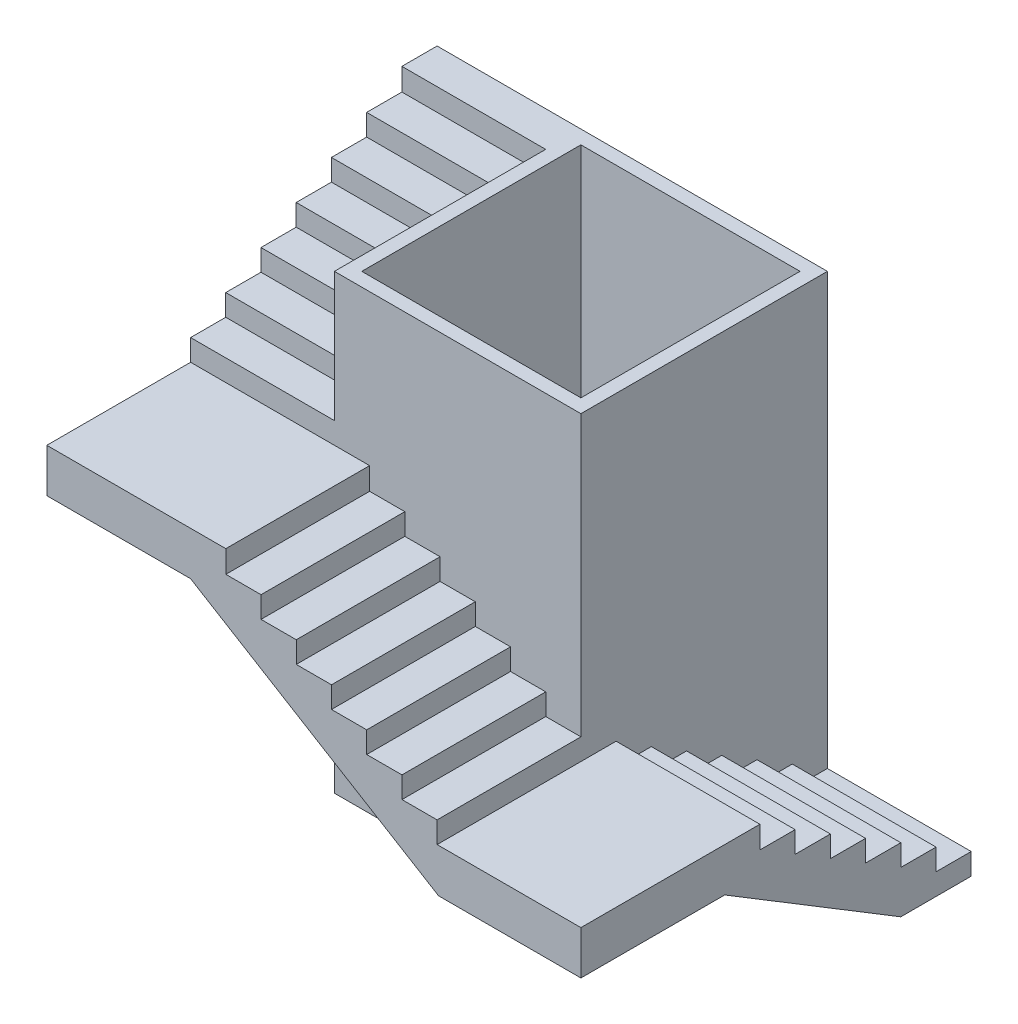
SolidWorks part; units mm, degrees
ref_plane "Front Plane" through (0, 0, 0) normal (0, 0, 1) x (1, 0, 0)
ref_plane "Top Plane" through (0, 0, 0) normal (0, 1, 0) x (1, 0, 0)
ref_plane "Right Plane" through (0, 0, 0) normal (1, 0, 0) x (0, 0, -1)
sketch "Sketch1" plane through (0, 0, 0) normal (0, 1, 0) x (1, 0, 0)
  line L1 (-9372.6, 3048) -> (9372.6, 3048)
  line L2 (-9372.6, 3048) -> (-9372.6, -3048)
  line L3 (-9372.6, -3048) -> (9372.6, -3048)
  line L4 (9372.6, 3048) -> (9372.6, -3048)
  line L5 (-9372.6, 3048) -> (9372.6, -3048) construction
  line L6 (-9372.6, -3048) -> (9372.6, 3048) construction
  line L7 (-914.4, -1066.8) -> (914.4, -1066.8)
  line L8 (-914.4, -1066.8) -> (-914.4, -2895.6)
  line L9 (-914.4, -2895.6) -> (914.4, -2895.6)
  line L10 (914.4, -1066.8) -> (914.4, -2895.6)
  line L11 (-914.4, -1066.8) -> (914.4, -2895.6) construction
  line L12 (-914.4, -2895.6) -> (914.4, -1066.8) construction
  line L13 (-1981.2, -3962.4) -> (1981.2, -3962.4)
  line L16 (-1981.2, -1066.8) -> (1981.2, -1066.8)
  line L17 (-1981.2, -1066.8) -> (-1981.2, -3962.4)
  line L18 (-1981.2, 0) -> (-1981.2, -3962.4) construction
  line L19 (1981.2, 342.9) -> (1981.2, -3962.4)
  line L20 (1981.2, 0) -> (1981.2, -3962.4) construction
  line L21 (-1981.2, 0) -> (1981.2, 0) construction
  line L22 (-914.4, 228.6) -> (1981.2, 228.6) construction
  line L23 (-1977.0221, -3048) -> (-9372.6, -3048) construction
  line L24 (-5562.6, 1828.8) -> (-5562.6, 1808.9756) construction
  line L25 (-1981.2, 3048) -> (-1981.2, -1066.8)
  line L26 (-9144, 1828.8) -> (-1981.2, 1828.8) construction
  line L35 (-9144, 2819.4) -> (9144, 2819.4)
  line L36 (9144, 2819.4) -> (9144, -2819.4)
  line L37 (-9144, -2819.4) -> (9144, -2819.4)
  line L38 (-9144, 2819.4) -> (-9144, -2819.4)
  line L43 (-1981.2, 342.9) -> (2257.9209, 342.9) construction
  line L48 (-5448.3, 1828.8) -> (-5448.3, 1771.8049)
  line L49 (-1981.2, 228.6) -> (2257.9209, 228.6) construction
  line L50 (-914.4, 114.3) -> (1981.2, 114.3)
  line L51 (-1981.2, 114.3) -> (2257.9209, 114.3) construction
  line L52 (-914.4, 342.9) -> (1981.2, 342.9)
  line L53 (-9144, 1524) -> (-5562.6, 1524) construction
  line L54 (-5562.6, 1524) -> (-5562.6, -2819.4) construction
  line L59 (5562.6, 228.6) -> (1981.2, 228.6)
  line L60 (-9372.6, 3048) -> (-5562.6, 3048) construction
  line L61 (-5448.3, 1828.8) -> (-5448.3, -2819.4) construction
  line L62 (-9372.6, 3048) -> (-9372.6, 1524) construction
  line L63 (-5562.6, 1828.8) -> (-5562.6, -2819.4) construction
  line L64 (-9372.6, 1524) -> (-5562.6, 1524) construction
  line L65 (-5562.6, 3048) -> (-5562.6, 1524) construction
  line L70 (9372.6, -3048) -> (5562.6, -3048)
  line L71 (9372.6, -3048) -> (9372.6, 342.9)
  line L73 (5562.6, -3048) -> (5562.6, 228.6)
  line L74 (1981.2, 228.6) -> (1981.2, 2819.4)
  line L75 (1981.2, 2819.4) -> (8001, 2819.4)
  line L76 (8001, 2819.4) -> (8001, 228.6)
  line L77 (-914.4, -1066.8) -> (-914.4, 342.9)
  line L78 (-5613.4, 3048) -> (-5613.4, 1574.8)
  line L79 (-9144, 1473.2) -> (-5613.4, 1473.2)
  line L80 (-5613.4, 1473.2) -> (-5613.4, -2819.4)
  line L81 (-5511.8, 3048) -> (-5511.8, 1524)
  line L82 (-9144, 1574.8) -> (-5613.4, 1574.8)
  line L83 (-5511.8, 1574.8) -> (-5511.8, -2819.4)
  line L84 (-5613.4, 3048) -> (-5613.4, 1524) construction
  line L85 (-812.8, -1168.4) -> (812.8, -1168.4)
  line L86 (-9144, 1574.8) -> (-5511.8, 1574.8) construction
  line L87 (812.8, -1168.4) -> (812.8, -2794)
  line L88 (-812.8, -2794) -> (812.8, -2794)
  line L89 (-812.8, -1168.4) -> (-812.8, -2794)
  line L90 (-1143, 342.9) -> (-1143, -1066.8)
  line L91 (-1143, 342.9) -> (-914.4, 342.9)
  line L92 (1981.2, 1206.5) -> (3810, 1206.5)
  line L93 (3810, 1206.5) -> (3810, 2819.4)
  line L94 (5676.9, -3048) -> (5676.9, 342.9)
  line L95 (5676.9, 342.9) -> (1981.2, 342.9)
  line L96 (5448.3, -3048) -> (5448.3, 114.3)
  line L97 (5448.3, 114.3) -> (1981.2, 114.3)
  line L98 (7950.2, 2819.4) -> (7950.2, 228.6)
  line L99 (8051.8, 2819.4) -> (8051.8, 228.6)
  line L100 (1981.2, 1308.1) -> (3810, 1308.1)
  line L101 (3708.4, 1206.5) -> (3708.4, 2819.4)
  line L102 (5676.9, 342.9) -> (9144, 342.9)
  line L103 (5676.9, 241.3) -> (9144, 241.3)
  line L104 (1879.6, 228.6) -> (1879.6, 2819.4)
  point P0 (0, 0)
  point P6 (0, -1981.2)
  point P18 (0, -1066.8)
  point P21 (533.4, 228.6)
  point P52 (0, 2819.4)
  dimension "D1" = 18745.2
  dimension "D2" = 6096
  dimension "D3" = 1828.8
  dimension "D4" = 1828.8
  dimension "D5" = 914.4
  dimension "D7" = 1143
  dimension "D8" = 1219.2
  dimension "D9" = 3810
  dimension "D10" = 1524
  dimension "D13" = 114.3
  dimension "D11" = 3810
  dimension "D14" = 114.3
  dimension "D16" = 3810
  dimension "D17" = 101.6
  dimension "D18" = 50.8
  dimension "D19" = 50.8
  dimension "D21" = 228.6
  dimension "D22" = 1828.8
  dimension "D23" = 863.6
  dimension "D30" = 101.6
  dimension "D6" = 1066.8
  dimension "D12" = 228.6
  dimension "D15" = 114.3
  dimension "D20" = 101.6
  dimension "D24" = 114.3
  dimension "D25" = 114.3
  dimension "D26" = 50.8
  dimension "D27" = 50.8
  dimension "D28" = 101.6
  dimension "D29" = 101.6
ref_plane "Plane1" through (0, 3962.4, 0) normal (0, 1, 0) x (1, 0, 0)
sketch "Sketch2" plane through (0, 3962.4, 0) normal (0, 1, 0) x (1, 0, 0)
  line L0 (-9372.6, 3048) -> (9372.6, 3048)
  line L1 (-9372.6, 3048) -> (-9372.6, -3048)
  line L2 (-9372.6, -3048) -> (9372.6, -3048)
  line L3 (9372.6, 3048) -> (9372.6, -3048)
  line L4 (-9372.6, 3048) -> (9372.6, -3048) construction
  line L5 (-9372.6, -3048) -> (9372.6, 3048) construction
  line L6 (-914.4, -1066.8) -> (914.4, -1066.8)
  line L7 (-914.4, -1066.8) -> (-914.4, -2895.6)
  line L8 (-914.4, -2895.6) -> (914.4, -2895.6)
  line L9 (914.4, -1066.8) -> (914.4, -2895.6)
  line L10 (-914.4, -1066.8) -> (914.4, -2895.6) construction
  line L11 (-914.4, -2895.6) -> (914.4, -1066.8) construction
  line L12 (-1981.2, -3962.4) -> (1981.2, -3962.4)
  line L13 (-1981.2, -1066.8) -> (1981.2, -1066.8)
  line L14 (-1981.2, -1066.8) -> (-1981.2, -3962.4)
  line L15 (1981.2, -1066.8) -> (1981.2, -3962.4)
  line L16 (-1981.2, 152.4) -> (2257.9209, 152.4) construction
  line L17 (-2099.6292, -3048) -> (-9372.6, -3048) construction
  line L18 (-5562.6, 1828.8) -> (-5562.6, -2819.4) construction
  line L19 (-9144, 1828.8) -> (-1981.2, 1828.8) construction
  line L20 (-9144, 2819.4) -> (8898.7858, 2819.4)
  line L21 (8898.7858, 2819.4) -> (8898.7858, -2819.4)
  line L22 (-9144, -2819.4) -> (8898.7858, -2819.4)
  line L23 (-9144, 2819.4) -> (-9144, -2819.4)
  line L24 (-914.4, -2895.6) -> (914.4, -2895.6) construction
  line L25 (-9372.6, 3048) -> (-6781.8, 3048)
  line L26 (-9372.6, 3048) -> (-9372.6, 1524)
  line L27 (-9372.6, 1524) -> (-6781.8, 1524)
  line L28 (-6781.8, 3048) -> (-6781.8, 1524)
  line L32 (0, 0) -> (0, 1033.0674) construction
  line L33 (-884.6071, 2819.4) -> (-884.6071, 1485.9)
  line L34 (-884.6071, 1485.9) -> (639.3929, 1485.9)
  line L35 (639.3929, 2819.4) -> (639.3929, 1485.9)
  line L36 (-253.2357, 3048) -> (639.3929, 1485.9) construction
  line L37 (-884.6071, 1485.9) -> (8.0215, 3048) construction
  line L38 (9144, 1828.8) -> (1981.2, 1828.8) construction
  line L39 (5562.6, 1828.8) -> (5562.6, -2819.4) construction
  line L42 (-1981.2, 1828.8) -> (-1981.2, -1066.8)
  line L43 (1981.2, 1828.8) -> (1981.2, -1066.8)
  line L44 (-9372.6, -3048) -> (9372.6, -3048) construction
  line L45 (9372.6, 3048) -> (9372.6, -3048) construction
  point P0 (0, 0)
  point P5 (0, -1981.2)
  point P15 (0, -1066.8)
  point P18 (138.3605, 152.4)
  point P43 (-122.6071, 2819.4)
  point P56 (0, 0)
  dimension "D1" = 18745.2
  dimension "D2" = 6096
  dimension "D3" = 1828.8
  dimension "D4" = 1828.8
  dimension "D5" = 1219.2
  dimension "D6" = 1219.2
  dimension "D7" = 1524
  dimension "D8" = 2590.8
  dimension "D9" = 914.4
  dimension "D11" = 228.6
extrude "Boss-Extrude1" add sketch "Sketch1" along normal blind 3352.8 contours L8 L37 L10 L7 L89 L85 L87 L88 | L37 L8 L9 L10
sketch "Sketch3" plane through (914.4, 0, 0) normal (1, 0, 0) x (0, 0, -1)
  line L0 (-1066.8, 0) -> (-1066.8, 237.4907)
  line L1 (-1066.8, 3352.8) -> (-1066.8, 0) construction
  line L2 (-2895.6, 1117.6) -> (-1066.8, 1117.6) construction
  line L3 (-2895.6, 3352.8) -> (-2895.6, 0) construction
  line L4 (-2634.3429, 1117.6) -> (-2634.3429, 0) construction
  line L5 (2819.4, 0) -> (-2819.4, 0) construction
  line L6 (-2372.9769, 1117.6) -> (-2372.9769, 0) construction
  line L7 (-2111.6109, 1117.6) -> (-2111.6109, 0) construction
  line L8 (-1850.2449, 1117.6) -> (-1850.2449, 0) construction
  line L9 (-1588.8789, 1117.6) -> (-1588.8789, 0) construction
  line L10 (-1327.5129, 1117.6) -> (-1327.5129, 0) construction
  line L11 (-1066.1469, 1117.6) -> (-1066.1469, 0) construction
  line L12 (-2895.6, 2235.2) -> (-2895.6, 0)
  line L13 (-2895.6, 952.5) -> (-1066.1469, 952.5) construction
  line L14 (-2895.6, 793.75) -> (-1066.1469, 793.75) construction
  line L15 (-2895.6, 635) -> (-1066.1469, 635) construction
  line L16 (-2895.6, 476.25) -> (-1066.1469, 476.25) construction
  line L17 (-2895.6, 317.5) -> (-1066.1469, 317.5) construction
  line L18 (-2895.6, 158.75) -> (-1066.1469, 158.75) construction
  line L19 (-2895.6, 0) -> (-1066.1469, 0) construction
  line L20 (-2895.6, 1117.6) -> (-2634.3429, 1117.6)
  line L21 (-2634.3429, 1117.6) -> (-2634.3429, 952.5)
  line L22 (-2634.3429, 952.5) -> (-2372.9769, 952.5)
  line L23 (-2372.9769, 952.5) -> (-2372.9769, 793.75)
  line L24 (-2372.9769, 793.75) -> (-2111.6109, 793.75)
  line L25 (-2111.6109, 793.75) -> (-2111.6109, 635)
  line L26 (-2111.6109, 635) -> (-1850.2449, 635)
  line L27 (-1850.2449, 635) -> (-1850.2449, 476.25)
  line L28 (-1850.2449, 476.25) -> (-1588.8789, 476.25)
  line L29 (-1588.8789, 476.25) -> (-1588.8789, 317.5)
  line L30 (-1588.8789, 317.5) -> (-1327.5129, 317.5)
  line L31 (-1327.5129, 317.5) -> (-1327.5129, 158.75)
  line L32 (-1327.5129, 158.75) -> (-1066.1469, 158.75)
  line L33 (-2895.6, 793.75) -> (-1588.8789, 0)
  point P29 (-2895.6, 1117.6)
  point P32 (-2895.6, 952.5)
  line M12 (-2895.6, 0) -> (-1066.8, 0)
  line M13 (-1066.8, 0) -> (-1066.8, 3352.8)
  dimension "D1" = 261.2571
  dimension "D3" = 165.1
  dimension "D4" = 7
  dimension "D2" = 7
extrude "Boss-Extrude2" add sketch "Sketch3" along normal blind 1066.8 contours L12 L33 L32 L31 L30 L29 L28 L27 L26 L25 L24 L23 L22 L21 L20 M12 M13
sketch "Sketch4" plane through (0, 0, 2895.6) normal (0, 0, 1) x (1, 0, 0)
  line L0 (914.4, 1117.6) -> (-914.4, 1117.6)
  line L1 (-914.4, 3352.8) -> (-914.4, 0) construction
  line L2 (914.4, 1117.6) -> (914.4, 1355.0907)
  line L3 (-914.4, 2235.2) -> (914.4, 2235.2) construction
  line L4 (-653.1429, 2235.2) -> (-653.1429, 1117.6) construction
  line L5 (-391.7769, 2235.2) -> (-391.7769, 1117.6) construction
  line L6 (-130.4109, 2235.2) -> (-130.4109, 1117.6) construction
  line L7 (130.9551, 2235.2) -> (130.9551, 1117.6) construction
  line L8 (392.3211, 2235.2) -> (392.3211, 1117.6) construction
  line L9 (653.6871, 2235.2) -> (653.6871, 1117.6) construction
  line L10 (915.0531, 2235.2) -> (915.0531, 1117.6) construction
  line L11 (-914.4, 3352.8) -> (-914.4, 1117.6)
  line L12 (-914.4, 2070.1) -> (915.0531, 2070.1) construction
  line L13 (-914.4, 1911.35) -> (915.0531, 1911.35) construction
  line L14 (-914.4, 1752.6) -> (915.0531, 1752.6) construction
  line L15 (-914.4, 1593.85) -> (915.0531, 1593.85) construction
  line L16 (-914.4, 1435.1) -> (915.0531, 1435.1) construction
  line L17 (-914.4, 1276.35) -> (915.0531, 1276.35) construction
  line L18 (-914.4, 1117.6) -> (915.0531, 1117.6) construction
  line L19 (-914.4, 2235.2) -> (-653.1429, 2235.2)
  line L20 (-653.1429, 2235.2) -> (-653.1429, 2070.1)
  line L21 (-653.1429, 2070.1) -> (-391.7769, 2070.1)
  line L22 (-391.7769, 2070.1) -> (-391.7769, 1911.35)
  line L23 (-391.7769, 1911.35) -> (-130.4109, 1911.35)
  line L24 (-130.4109, 1911.35) -> (-130.4109, 1752.6)
  line L25 (-130.4109, 1752.6) -> (130.9551, 1752.6)
  line L26 (130.9551, 1752.6) -> (130.9551, 1593.85)
  line L27 (130.9551, 1593.85) -> (392.3211, 1593.85)
  line L28 (392.3211, 1593.85) -> (392.3211, 1435.1)
  line L29 (392.3211, 1435.1) -> (653.6871, 1435.1)
  line L30 (653.6871, 1435.1) -> (653.6871, 1276.35)
  line L31 (653.6871, 1276.35) -> (915.0531, 1276.35)
  line L32 (-914.4, 1911.35) -> (392.3211, 1117.6)
  line L41 (-914.4, 0) -> (914.4, 0)
  line L42 (914.4, 0) -> (914.4, 793.75)
  line L43 (914.4, 793.75) -> (1981.2, 793.75)
  line L44 (1981.2, 793.75) -> (1981.2, 1117.6)
  line L45 (1981.2, 1117.6) -> (914.4, 1117.6)
  line L46 (914.4, 1117.6) -> (914.4, 3352.8)
  line L47 (914.4, 3352.8) -> (-914.4, 3352.8)
  line L48 (-914.4, 3352.8) -> (-914.4, 0)
  line L49 (-914.4, 0) -> (914.4, 0)
  line L50 (914.4, 0) -> (914.4, 793.75)
  line L51 (914.4, 793.75) -> (1981.2, 793.75)
  line L52 (1981.2, 793.75) -> (1981.2, 1117.6)
  line L53 (1981.2, 1117.6) -> (914.4, 1117.6)
  line L54 (914.4, 1117.6) -> (914.4, 3352.8)
  line L55 (914.4, 3352.8) -> (-914.4, 3352.8)
  line L56 (-914.4, 3352.8) -> (-914.4, 0)
  point P26 (-914.4, 2235.2)
  point P29 (-914.4, 2070.1)
  line M18 (914.4, 1117.6) -> (914.4, 3352.8)
  dimension "D1" = 165.1
  dimension "D3" = 158.75
  dimension "D2" = 0
extrude "Boss-Extrude3" add sketch "Sketch4" along normal blind 1066.8 contours L11 L32 L0 L31 L30 L29 L28 L27 L26 L25 L24 L23 L22 L21 L20 L19 M18
sketch "Sketch5" plane through (0, 1117.6, 0) normal (0, 1, 0) x (1, 0, 0)
  line L1 (914.4, -2895.6) -> (1981.2, -2895.6)
  line L2 (914.4, -2895.6) -> (914.4, -3962.4)
  line L3 (914.4, -3962.4) -> (1981.2, -3962.4)
  line L4 (1981.2, -2895.6) -> (1981.2, -3962.4)
  line L8 (914.4, -2895.6) -> (392.3211, -2895.6)
  line L9 (914.4, -3962.4) -> (914.4, -2895.6)
  line L10 (392.3211, -3962.4) -> (914.4, -3962.4)
  line L11 (392.3211, -2895.6) -> (392.3211, -3962.4)
  line L12 (914.4, -2895.6) -> (392.3211, -2895.6)
  line L13 (914.4, -3962.4) -> (914.4, -2895.6)
  line L14 (392.3211, -3962.4) -> (914.4, -3962.4)
  line L15 (392.3211, -2895.6) -> (392.3211, -3962.4)
  line M6 (914.4, -2895.6) -> (1981.2, -2895.6)
  dimension "D1" = 0
extrude "Boss-Extrude5" add sketch "Sketch5" against normal blind 323.85 contours L4 L2 L3 M6 | L12 L15 L14 L2
sketch "Sketch6" plane through (-914.4, 0, 0) normal (-1, 0, 0) x (0, 0, 1)
  line L0 (2895.6, 2235.2) -> (1066.8, 2235.2)
  line L1 (1066.8, 3352.8) -> (1066.8, 0) construction
  line L2 (2895.6, 2235.2) -> (2895.6, 2472.6907)
  line L3 (1066.8, 3352.8) -> (2895.6, 3352.8) construction
  line L4 (1328.0571, 3352.8) -> (1328.0571, 2235.2) construction
  line L5 (1589.4231, 3352.8) -> (1589.4231, 2235.2) construction
  line L6 (1850.7891, 3352.8) -> (1850.7891, 2235.2) construction
  line L7 (2112.1551, 3352.8) -> (2112.1551, 2235.2) construction
  line L8 (2373.5211, 3352.8) -> (2373.5211, 2235.2) construction
  line L9 (2634.8871, 3352.8) -> (2634.8871, 2235.2) construction
  line L10 (2896.2531, 3352.8) -> (2896.2531, 2235.2) construction
  line L11 (1066.8, 4470.4) -> (1066.8, 2235.2)
  line L12 (1066.8, 3187.7) -> (2896.2531, 3187.7) construction
  line L13 (1066.8, 3028.95) -> (2896.2531, 3028.95) construction
  line L14 (1066.8, 2870.2) -> (2896.2531, 2870.2) construction
  line L15 (1066.8, 2711.45) -> (2896.2531, 2711.45) construction
  line L16 (1066.8, 2552.7) -> (2896.2531, 2552.7) construction
  line L17 (1066.8, 2393.95) -> (2896.2531, 2393.95) construction
  line L18 (1066.8, 2235.2) -> (2896.2531, 2235.2) construction
  line L19 (1066.8, 3352.8) -> (1328.0571, 3352.8)
  line L20 (1328.0571, 3352.8) -> (1328.0571, 3187.7)
  line L21 (1328.0571, 3187.7) -> (1589.4231, 3187.7)
  line L22 (1589.4231, 3187.7) -> (1589.4231, 3028.95)
  line L23 (1589.4231, 3028.95) -> (1850.7891, 3028.95)
  line L24 (1850.7891, 3028.95) -> (1850.7891, 2870.2)
  line L25 (1850.7891, 2870.2) -> (2112.1551, 2870.2)
  line L26 (2112.1551, 2870.2) -> (2112.1551, 2711.45)
  line L27 (2112.1551, 2711.45) -> (2373.5211, 2711.45)
  line L28 (2373.5211, 2711.45) -> (2373.5211, 2552.7)
  line L29 (2373.5211, 2552.7) -> (2634.8871, 2552.7)
  line L30 (2634.8871, 2552.7) -> (2634.8871, 2393.95)
  line L31 (2634.8871, 2393.95) -> (2896.2531, 2393.95)
  line L32 (1066.8, 3028.95) -> (2373.5211, 2235.2)
  point P26 (1066.8, 3352.8)
  point P29 (1066.8, 3187.7)
  line M7 (2895.6, 2235.2) -> (2895.6, 3352.8)
  dimension "D1" = 165.1
extrude "Boss-Extrude6" add sketch "Sketch6" along normal blind 1066.8 contours L11 L32 L0 L31 L30 L29 L28 L27 L26 L25 L24 L23 L22 L21 L20 L19 M7
sketch "Sketch7" plane through (0, 2235.2, 0) normal (0, -1, 0) x (1, 0, 0)
  line L0 (-1981.2, 1066.8) -> (-1981.2, 3962.4) construction
  line L1 (-1981.2, 3962.4) -> (1981.2, 3962.4) construction
  line L2 (-1981.2, 1066.8) -> (-1981.2, 3962.4)
  line L3 (-1981.2, 3962.4) -> (1981.2, 3962.4)
  line L4 (-914.4, 2373.5211) -> (-914.4, 2895.6)
  line L5 (-914.4, 2895.6) -> (-1981.2, 2895.6)
  line L6 (-1981.2, 2895.6) -> (-1981.2, 2373.5211)
  line L7 (-1981.2, 2373.5211) -> (-914.4, 2373.5211)
  line L8 (-914.4, 2373.5211) -> (-914.4, 2895.6)
  line L9 (-914.4, 2895.6) -> (-1981.2, 2895.6)
  line L10 (-1981.2, 2895.6) -> (-1981.2, 2373.5211)
  line L11 (-1981.2, 2373.5211) -> (-914.4, 2373.5211)
  line L12 (-914.4, 3962.4) -> (-914.4, 2895.6)
  line M5 (-914.4, 2373.5211) -> (-914.4, 2895.6)
  line M6 (-914.4, 2895.6) -> (-1981.2, 2895.6)
  line M7 (-1981.2, 2895.6) -> (-1981.2, 2373.5211)
  line M8 (-1981.2, 2373.5211) -> (-914.4, 2373.5211)
  dimension "D1" = 0
extrude "Boss-Extrude7" add sketch "Sketch7" along normal blind 323.85 contours L12 L3 L2 M6 | M8 M5 M6 M7
sketch "Sketch8" plane through (0, 0, 3962.4) normal (0, 0, 1) x (1, 0, 0)
  line L0 (-914.4, 1911.35) -> (392.3211, 1117.6) construction
  line L1 (-914.4, 1911.35) -> (925.4634, 793.75)
  line L2 (392.3211, 793.75) -> (1981.2, 793.75) construction
  line L3 (392.3211, 793.75) -> (1981.2, 793.75)
  line L4 (392.3211, 793.75) -> (392.3211, 1117.6) construction
  line L5 (392.3211, 793.75) -> (392.3211, 1117.6)
  line M5 (392.3211, 1117.6) -> (392.3211, 793.75)
  line M6 (392.3211, 793.75) -> (1981.2, 793.75)
extrude "Cut-Extrude1" cut sketch "Sketch8" against normal blind 1066.8 contours L1 M5 M6
sketch "Sketch9" plane through (-1981.2, 0, 0) normal (-1, 0, 0) x (0, 0, 1)
  line L20 (1066.8, 3352.8) -> (1066.8, 3028.95)
  line L21 (1066.8, 3028.95) -> (2373.5211, 2235.2)
  line L22 (2373.5211, 2235.2) -> (2373.5211, 1911.35)
  line L23 (2373.5211, 1911.35) -> (3962.4, 1911.35)
  line L24 (3962.4, 1911.35) -> (3962.4, 2235.2)
  line L25 (3962.4, 2235.2) -> (2895.6, 2235.2)
  line L26 (2895.6, 2235.2) -> (2895.6, 2393.95)
  line L27 (2895.6, 2393.95) -> (2634.8871, 2393.95)
  line L28 (2634.8871, 2393.95) -> (2634.8871, 2552.7)
  line L29 (2634.8871, 2552.7) -> (2373.5211, 2552.7)
  line L30 (2373.5211, 2552.7) -> (2373.5211, 2711.45)
  line L31 (2373.5211, 2711.45) -> (2112.1551, 2711.45)
  line L32 (2112.1551, 2711.45) -> (2112.1551, 2870.2)
  line L33 (2112.1551, 2870.2) -> (1850.7891, 2870.2)
  line L34 (1850.7891, 2870.2) -> (1850.7891, 3028.95)
  line L35 (1850.7891, 3028.95) -> (1589.4231, 3028.95)
  line L36 (1589.4231, 3028.95) -> (1589.4231, 3187.7)
  line L37 (1589.4231, 3187.7) -> (1328.0571, 3187.7)
  line L38 (1328.0571, 3187.7) -> (1328.0571, 3352.8)
  line L39 (1328.0571, 3352.8) -> (1066.8, 3352.8)
  line L40 (1066.8, 3352.8) -> (1066.8, 3028.95)
  line L41 (1066.8, 3028.95) -> (2906.6634, 1911.35)
  line L42 (2373.5211, 2235.2) -> (2373.5211, 1911.35)
  line L43 (2373.5211, 1911.35) -> (3962.4, 1911.35)
  line L44 (3962.4, 1911.35) -> (3962.4, 2235.2)
  line L45 (3962.4, 2235.2) -> (2895.6, 2235.2)
  line L46 (2895.6, 2235.2) -> (2895.6, 2393.95)
  line L47 (2895.6, 2393.95) -> (2634.8871, 2393.95)
  line L48 (2634.8871, 2393.95) -> (2634.8871, 2552.7)
  line L49 (2634.8871, 2552.7) -> (2373.5211, 2552.7)
  line L50 (2373.5211, 2552.7) -> (2373.5211, 2711.45)
  line L51 (2373.5211, 2711.45) -> (2112.1551, 2711.45)
  line L52 (2112.1551, 2711.45) -> (2112.1551, 2870.2)
  line L53 (2112.1551, 2870.2) -> (1850.7891, 2870.2)
  line L54 (1850.7891, 2870.2) -> (1850.7891, 3028.95)
  line L55 (1850.7891, 3028.95) -> (1589.4231, 3028.95)
  line L56 (1589.4231, 3028.95) -> (1589.4231, 3187.7)
  line L57 (1589.4231, 3187.7) -> (1328.0571, 3187.7)
  line L58 (1328.0571, 3187.7) -> (1328.0571, 3352.8)
  line L59 (1328.0571, 3352.8) -> (1066.8, 3352.8)
  line M23 (2373.5211, 2235.2) -> (2373.5211, 1911.35)
  line M24 (2373.5211, 1911.35) -> (3962.4, 1911.35)
  dimension "D1" = 0
extrude "Cut-Extrude2" cut sketch "Sketch9" against normal blind 1066.8 contours L41 M23 M24
sketch "Sketch10" plane through (0, 0, 0) normal (0, 1, 0) x (1, 0, 0)
  line L0 (-1981.2, -1066.8) -> (1981.2, -1066.8) construction
  line L1 (-914.4, -1066.8) -> (-914.4, 342.9) construction
  line L2 (9372.6, -3048) -> (5562.6, -3048) construction
  line L3 (5562.6, -3048) -> (5562.6, 228.6) construction
  line L4 (5562.6, 228.6) -> (1981.2, 228.6) construction
  line L5 (1981.2, 228.6) -> (1981.2, 2819.4) construction
  line L6 (1981.2, 2819.4) -> (8001, 2819.4) construction
  line L7 (8001, 2819.4) -> (8001, 228.6) construction
  line L10 (-1981.2, 3048) -> (-1981.2, -1066.8) construction
  line L11 (-1981.2, -1066.8) -> (-1981.2, -3962.4) construction
  line L12 (-1981.2, -3962.4) -> (1981.2, -3962.4) construction
  line L13 (1981.2, 342.9) -> (1981.2, -3962.4) construction
  line L14 (-914.4, 342.9) -> (1981.2, 342.9) construction
  line L15 (-5613.4, 3048) -> (-5613.4, 1574.8) construction
  line L16 (-9144, 1574.8) -> (-5613.4, 1574.8) construction
  line L17 (-914.4, 114.3) -> (1981.2, 114.3) construction
  line L18 (1981.2, 1206.5) -> (3810, 1206.5) construction
  line L19 (3810, 1206.5) -> (3810, 2819.4) construction
  line L20 (-9144, 1473.2) -> (-5613.4, 1473.2) construction
  line L21 (-5613.4, 1473.2) -> (-5613.4, -2819.4) construction
  line L22 (-1143, 342.9) -> (-1143, -1066.8) construction
  line L23 (-1143, 342.9) -> (-914.4, 342.9) construction
  line L24 (-5511.8, 1574.8) -> (-5511.8, -2819.4) construction
  line L25 (-5511.8, 3048) -> (-5511.8, 1524) construction
  line L26 (5676.9, 241.3) -> (9144, 241.3) construction
  line L27 (5676.9, 342.9) -> (9144, 342.9) construction
  line L28 (3708.4, 1206.5) -> (3708.4, 2819.4) construction
  line L29 (1981.2, 1308.1) -> (3810, 1308.1) construction
  line L30 (8051.8, 2819.4) -> (8051.8, 228.6) construction
  line L31 (7950.2, 2819.4) -> (7950.2, 228.6) construction
  line L32 (5448.3, -3048) -> (5448.3, 114.3) construction
  line L33 (5448.3, 114.3) -> (1981.2, 114.3) construction
  line L34 (5676.9, 342.9) -> (1981.2, 342.9) construction
  line L35 (5676.9, -3048) -> (5676.9, 342.9) construction
  line L36 (1879.6, 228.6) -> (1879.6, 2819.4) construction
  line L37 (-914.4, -1066.8) -> (914.4, -1066.8) construction
  line L38 (914.4, -1066.8) -> (914.4, -2895.6) construction
  line L39 (-914.4, -2895.6) -> (914.4, -2895.6) construction
  line L40 (-914.4, -1066.8) -> (-914.4, -2895.6) construction
  line L41 (9372.6, 3048) -> (9372.6, -3048) construction
  line L42 (-9372.6, 3048) -> (9372.6, 3048) construction
  line L43 (-9372.6, 3048) -> (-9372.6, -3048) construction
  line L44 (-9372.6, -3048) -> (9372.6, -3048) construction
  line L45 (-9144, 2819.4) -> (9144, 2819.4) construction
  line L46 (9144, 2819.4) -> (9144, -2819.4) construction
  line L47 (-9144, -2819.4) -> (9144, -2819.4) construction
  line L48 (-9144, 2819.4) -> (-9144, -2819.4) construction
  line L49 (-812.8, -1168.4) -> (812.8, -1168.4) construction
  line L50 (812.8, -1168.4) -> (812.8, -2794) construction
  line L51 (-812.8, -2794) -> (812.8, -2794) construction
  line L52 (-812.8, -1168.4) -> (-812.8, -2794) construction
  line L53 (-1981.2, -1066.8) -> (1981.2, -1066.8)
  line L54 (-914.4, -1066.8) -> (-914.4, 342.9)
  line L55 (9372.6, -3048) -> (5562.6, -3048)
  line L56 (5562.6, -3048) -> (5562.6, 228.6)
  line L57 (5562.6, 228.6) -> (1981.2, 228.6)
  line L58 (1981.2, 228.6) -> (1981.2, 2819.4)
  line L59 (1981.2, 2819.4) -> (8001, 2819.4)
  line L60 (8001, 2819.4) -> (8001, 228.6)
  line L63 (-1981.2, 3048) -> (-1981.2, -1066.8)
  line L64 (-1981.2, -1066.8) -> (-1981.2, -3962.4)
  line L65 (-1981.2, -3962.4) -> (1981.2, -3962.4)
  line L66 (1981.2, 342.9) -> (1981.2, -3962.4)
  line L67 (-914.4, 342.9) -> (1981.2, 342.9)
  line L68 (-5613.4, 3048) -> (-5613.4, 1574.8)
  line L69 (-9144, 1574.8) -> (-5613.4, 1574.8)
  line L70 (-914.4, 114.3) -> (1981.2, 114.3)
  line L71 (1981.2, 1206.5) -> (3810, 1206.5)
  line L72 (3810, 1206.5) -> (3810, 2819.4)
  line L73 (-9144, 1473.2) -> (-5613.4, 1473.2)
  line L74 (-5613.4, 1473.2) -> (-5613.4, -2819.4)
  line L75 (-1143, 342.9) -> (-1143, -1066.8)
  line L76 (-1143, 342.9) -> (-914.4, 342.9)
  line L77 (-5511.8, 1574.8) -> (-5511.8, -2819.4)
  line L78 (-5511.8, 3048) -> (-5511.8, 1524)
  line L79 (5676.9, 241.3) -> (9144, 241.3)
  line L80 (5676.9, 342.9) -> (9144, 342.9)
  line L81 (3708.4, 1206.5) -> (3708.4, 2819.4)
  line L82 (1981.2, 1308.1) -> (3810, 1308.1)
  line L83 (8051.8, 2819.4) -> (8051.8, 228.6)
  line L84 (7950.2, 2819.4) -> (7950.2, 228.6)
  line L85 (5448.3, -3048) -> (5448.3, 114.3)
  line L86 (5448.3, 114.3) -> (1981.2, 114.3)
  line L87 (5676.9, 342.9) -> (1981.2, 342.9)
  line L88 (5676.9, -3048) -> (5676.9, 342.9)
  line L89 (1879.6, 342.9) -> (1879.6, 2819.4)
  line L90 (-914.4, -1066.8) -> (914.4, -1066.8)
  line L91 (914.4, -1066.8) -> (914.4, -2895.6)
  line L92 (-914.4, -2895.6) -> (914.4, -2895.6)
  line L93 (-914.4, -1066.8) -> (-914.4, -2895.6)
  line L94 (9372.6, 3048) -> (9372.6, -3048)
  line L95 (-9372.6, 3048) -> (9372.6, 3048)
  line L96 (-9372.6, 3048) -> (-9372.6, -3048)
  line L97 (-9372.6, -3048) -> (9372.6, -3048)
  line L98 (-9144, 2819.4) -> (9144, 2819.4)
  line L99 (9144, 2819.4) -> (9144, -2819.4)
  line L100 (-9144, -2819.4) -> (9144, -2819.4)
  line L101 (-9144, 2819.4) -> (-9144, -2819.4)
  line L102 (-812.8, -1168.4) -> (812.8, -1168.4)
  line L103 (812.8, -1168.4) -> (812.8, -2794)
  line L104 (-812.8, -2794) -> (812.8, -2794)
  line L105 (-812.8, -1168.4) -> (-812.8, -2794)
  point P8 (0, 0)
extrude "Boss-Extrude10" [suppressed] add sketch "Sketch10" along normal blind 3352.8 separate body contours L68 L98 L78 L95 | L69 L101 L73 L74 L100 L77 L78 L98 L68 | L101 L98 L68 L95 L96 L97 L64 L100 | L78 L98 L63 L95 | L100 L88 L55 L94 L95 L63 L98 L59 L99 | L76 L75 L53 L54 | L54 L70 L66 L58 L67 | L85 L100 L56 L57 L66 L86 | L56 L100 L88 L87 L58 L57 | L88 L79 L84 L80 | L100 L85 L97 L56 | L100 L56 L55 L88 | L99 L80 L83 L79 | L80 L84 L79 L60 | L83 L80 L60 L79 | L59 L84 L80 L60 | L81 L82 L72 L59 | L82 L81 L71 L72 | L82 L58 L71 L81 | L98 L89 L67 L58
equation "\"20fr\"=6265.24"
equation "\"6f\"=395.418"
